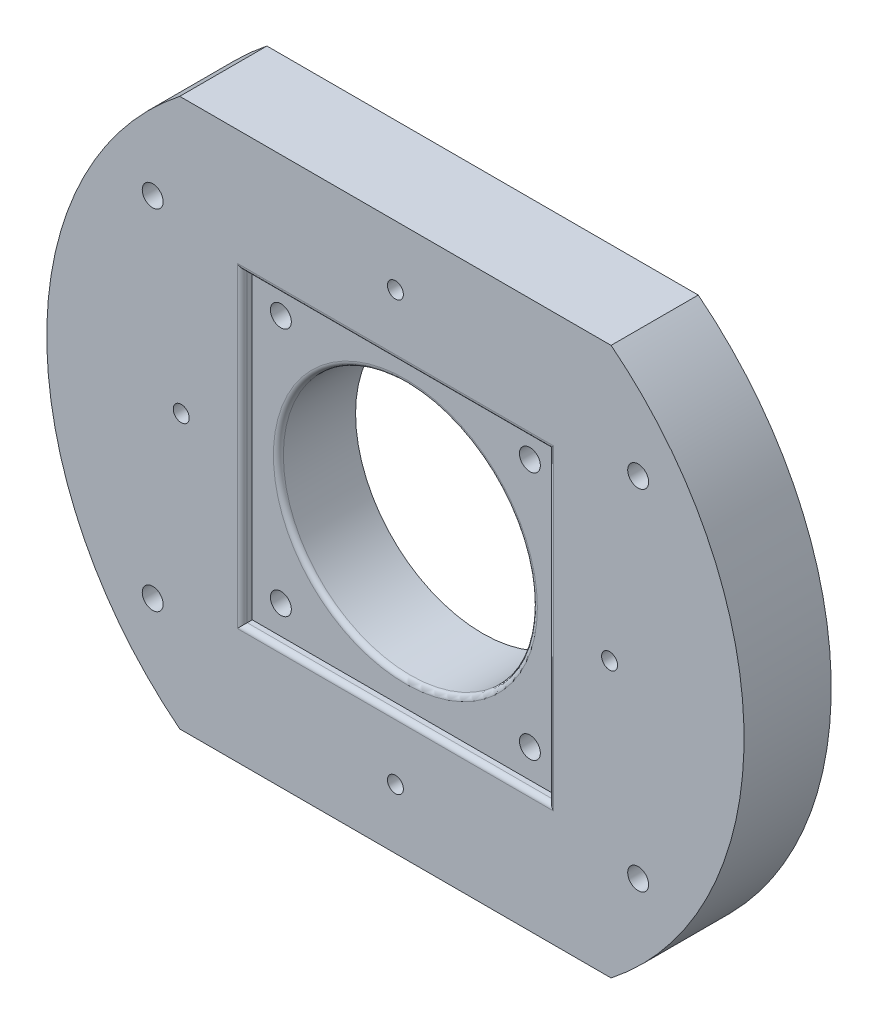
SolidWorks part; units mm, degrees
ref_plane "Front Plane" through (0, 0, 0) normal (0, 0, 1) x (1, 0, 0)
ref_plane "Top Plane" through (0, 0, 0) normal (0, 1, 0) x (1, 0, 0)
ref_plane "Right Plane" through (0, 0, 0) normal (1, 0, 0) x (0, 0, -1)
sketch "Sketch1" plane through (0, 0, 0) normal (0, 0, 1) x (1, 0, 0)
  line L1 (-25, 25) -> (25, 25) construction
  line L2 (-25, 25) -> (-25, -25) construction
  line L3 (-25, -25) -> (25, -25) construction
  line L4 (25, 25) -> (25, -25) construction
  line L5 (-25, 25) -> (25, -25) construction
  line L6 (-25, -25) -> (25, 25) construction
  circle A0 centre (0, 0) radius 70
  circle A1 centre (0, 0) radius 25.5
  circle A2 centre (-25, 25) radius 2.1
  circle A3 centre (25, 25) radius 2.1
  circle A4 centre (25, -25) radius 2.1
  circle A5 centre (-25, -25) radius 2.1
  dimension "D1" = 140
  dimension "D2" = 51
  dimension "D4" = 4.2
  dimension "D3" = 50
extrude "Boss-Extrude1" add sketch "Sketch1" along normal blind 17.5
sketch "Sketch2" plane through (0, 0, 17.5) normal (0, 0, 1) x (1, 0, 0)
  line L1 (-30.75, 30.75) -> (30.75, 30.75)
  line L2 (-30.75, 30.75) -> (-30.75, -30.75)
  line L3 (-30.75, -30.75) -> (30.75, -30.75)
  line L4 (30.75, 30.75) -> (30.75, -30.75)
  line L5 (-30.75, 30.75) -> (30.75, -30.75) construction
  line L6 (-30.75, -30.75) -> (30.75, 30.75) construction
  point P0 (0, 0)
  dimension "D1" = 61.5
extrude "Cut-Extrude1" cut sketch "Sketch2" against normal blind 2
sketch "Sketch3" plane through (0, 0, 17.5) normal (0, 0, 1) x (1, 0, 0)
  circle A0 centre (0, 0) radius 43 construction
  circle A1 centre (0, 43) radius 1.6
  circle A2 centre (-43, 0) radius 1.6
  circle A3 centre (43, 0) radius 1.6
  circle A4 centre (0, -43) radius 1.6
  dimension "D1" = 86
  dimension "D2" = 3.2
extrude "Cut-Extrude2" cut sketch "Sketch3" against normal through all
sketch "Sketch4" plane through (0, 0, 0) normal (0, 0, -1) x (-1, 0, 0)
  circle A0 centre (-25, 25) radius 3.5
  circle A1 centre (25, 25) radius 3.5
  circle A2 centre (25, -25) radius 3.5
  circle A3 centre (-25, -25) radius 3.5
  dimension "D1" = 7
extrude "Cut-Extrude3" cut sketch "Sketch4" against normal blind 6.2
sketch "Sketch5" plane through (0, 0, 0) normal (0, 0, -1) x (-1, 0, 0)
  line L0 (-43.3013, -55) -> (43.3013, -55)
  line L1 (0, -55) -> (0, -70) construction
  line L2 (-43.3013, 55) -> (43.3013, 55)
  line L3 (-48.734, 35) -> (48.734, 35) construction
  line L4 (-48.734, 35) -> (-48.734, -35) construction
  line L5 (-48.734, -35) -> (48.734, -35) construction
  line L6 (48.734, 35) -> (48.734, -35) construction
  line L7 (-48.734, 35) -> (48.734, -35) construction
  line L8 (-48.734, -35) -> (48.734, 35) construction
  circle A0 centre (0, 0) radius 70 construction
  arc A1 (-43.3013, -55) -> (43.3013, -55) centre (0, 0) ccw
  circle A2 centre (0, 0) radius 60 construction
  circle A3 centre (-48.734, 35) radius 2.1
  circle A4 centre (0, 60) radius 2.1 construction
  circle A5 centre (48.734, 35) radius 2.1
  circle A6 centre (48.734, -35) radius 2.1
  circle A7 centre (-48.734, -35) radius 2.1
  arc A8 (-43.3013, 55) -> (43.3013, 55) centre (0, 0) cw
  dimension "D1" = 15
  dimension "D2" = 120
  dimension "D4" = 4.2
  dimension "D3" = 70
extrude "Cut-Extrude4" cut sketch "Sketch5" against normal up to surface (17.5 mm away) up to face at (-41.4, 0, 17.5)
fillet "Fillet1" radius 1 9 edges at (0, -30.75, 17.5) (30.75, 0, 17.5) (0, 30.75, 17.5) (-30.75, 0, 17.5) (25.5, 0, 15.5) (21.5, 25, 0) (-28.5, 25, 0) (-28.5, -25, 0) (21.5, -25, 0)
